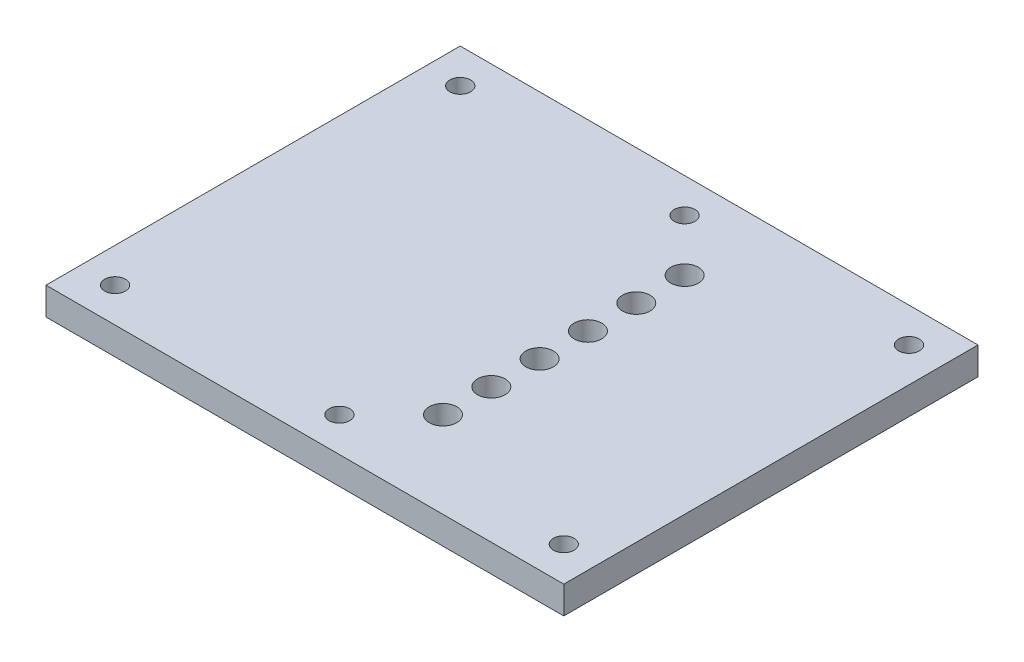
SolidWorks part; units mm, degrees
ref_plane "前视基准面" through (0, 0, 0) normal (0, 0, 1) x (1, 0, 0)
ref_plane "上视基准面" through (0, 0, 0) normal (0, 1, 0) x (1, 0, 0)
ref_plane "右视基准面" through (0, 0, 0) normal (1, 0, 0) x (0, 0, -1)
sketch "草图1" plane through (0, 0, 0) normal (0, 1, 0) x (1, 0, 0)
  line L1 (-37.5, 30) -> (37.5, 30)
  line L2 (-37.5, 30) -> (-37.5, -30)
  line L3 (-37.5, -30) -> (37.5, -30)
  line L4 (37.5, 30) -> (37.5, -30)
  line L5 (-37.5, 30) -> (37.5, -30) construction
  line L6 (-37.5, -30) -> (37.5, 30) construction
  point P0 (0, 0)
  dimension "D1" = 75
  dimension "D2" = 60
extrude "凸台-拉伸1" add sketch "草图1" along normal blind 4
sketch "草图2" plane through (0, 0, 0) normal (0, 1, 0) x (1, 0, 0)
  line L0 (37.5, 30) -> (-37.5, 30) construction
  line L1 (37.5, -30) -> (37.5, 30) construction
  circle A0 centre (7.5, 17.5) radius 2
  circle A1 centre (7.5, 10.5) radius 2
  circle A2 centre (7.5, 3.5) radius 2
  circle A3 centre (7.5, -3.5) radius 2
  circle A4 centre (7.5, -10.5) radius 2
  circle A5 centre (7.5, -17.5) radius 2
  dimension "D2" = 4
  dimension "D3" = 12.5
  dimension "D4" = 30
  dimension "D1" = 6
extrude "切除-拉伸1" cut sketch "草图2" along normal blind 4
sketch "草图3" plane through (0, 0, 0) normal (0, 1, 0) x (1, 0, 0)
  line L0 (-37.5, 30) -> (-37.5, -30) construction
  line L1 (37.5, 30) -> (-37.5, 30) construction
  line L2 (-10.2599, 0) -> (-24.0303, 0) construction
  line L3 (0, 30) -> (0, 12.6019) construction
  line L4 (37.5, -30) -> (37.5, 30) construction
  circle A0 centre (-32.5, 25) radius 1.5
  circle A1 centre (32.5, 25) radius 1.5
  circle A2 centre (32.5, -25) radius 1.5
  circle A3 centre (-32.5, -25) radius 1.5
  circle A4 centre (0, -25) radius 1.5
  circle A6 centre (0, 25) radius 1.5
  dimension "D1" = 3
  dimension "D2" = 5
  dimension "D3" = 5
  dimension "D4" = 37.5
  dimension "D5" = 2
extrude "切除-拉伸2" cut sketch "草图3" along normal through all
